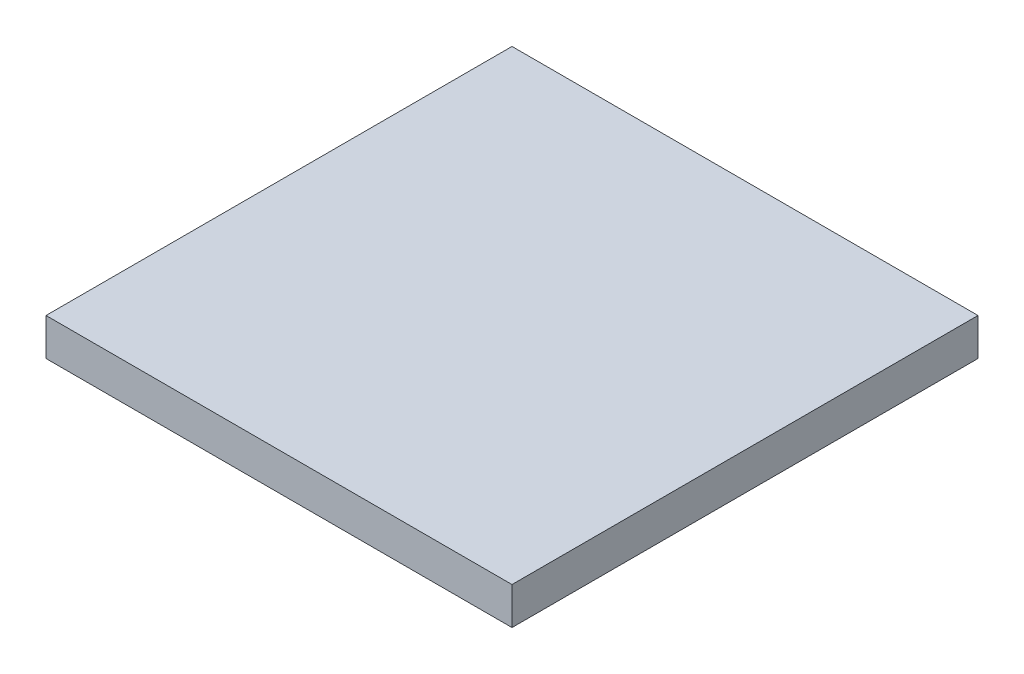
SolidWorks part; units mm, degrees
material "Mahogany"
ref_plane "Front Plane" through (0, 0, 0) normal (0, 0, 1) x (1, 0, 0)
ref_plane "Top Plane" through (0, 0, 0) normal (0, 1, 0) x (1, 0, 0)
ref_plane "Right Plane" through (0, 0, 0) normal (1, 0, 0) x (0, 0, -1)
sketch "Sketch1" plane through (0, 0, 0) normal (0, 1, 0) x (1, 0, 0)
  line L1 (0, 0) -> (37.5, 0)
  line L2 (0, 0) -> (0, 37.5)
  line L3 (0, 37.5) -> (37.5, 37.5)
  line L4 (37.5, 0) -> (37.5, 37.5)
  dimension "D1" = 37.5
  dimension "D2" = 37.5
extrude "Boss-Extrude1" add sketch "Sketch1" along normal blind 3
